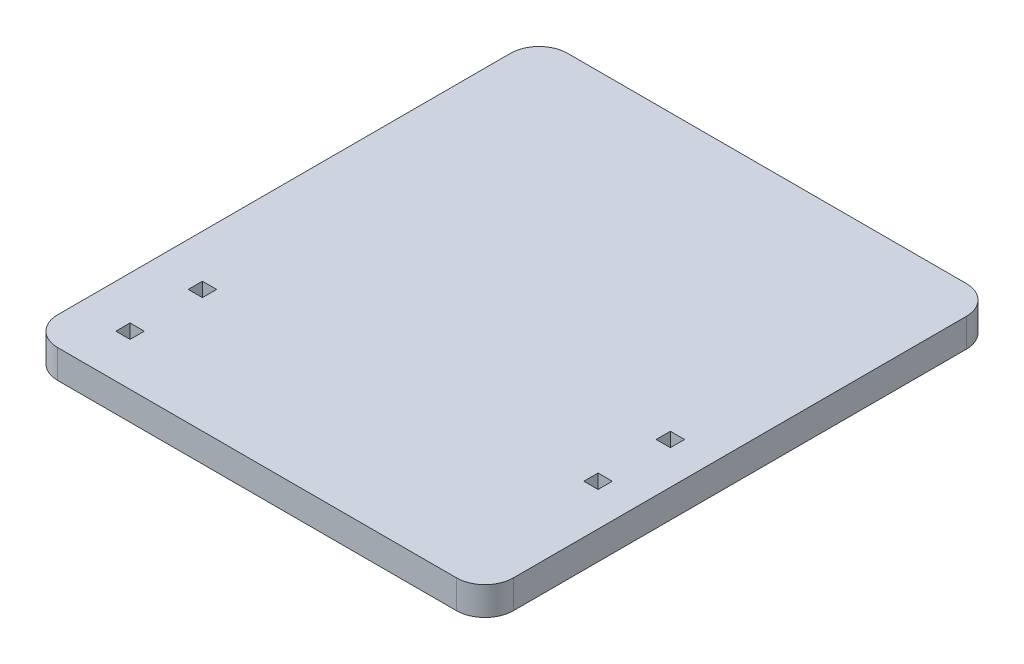
SolidWorks part; units mm, degrees
ref_plane "Front Plane" through (0, 0, 0) normal (0, 0, 1) x (1, 0, 0)
ref_plane "Top Plane" through (0, 0, 0) normal (0, 1, 0) x (1, 0, 0)
ref_plane "Right Plane" through (0, 0, 0) normal (1, 0, 0) x (0, 0, -1)
sketch "Sketch1" plane through (0, 0, 0) normal (0, 1, 0) x (1, 0, 0)
  line L1 (1, 0) -> (15, 0)
  line L2 (0, 1) -> (0, 16.9)
  line L3 (1, 17.9) -> (15, 17.9)
  line L4 (16, 1) -> (16, 16.9)
  line L5 (1.52, 1.52) -> (2.02, 1.52)
  line L6 (1.52, 1.52) -> (1.52, 2.02)
  line L7 (1.52, 2.02) -> (2.02, 2.02)
  line L8 (2.02, 1.52) -> (2.02, 2.02)
  line L9 (1.52, 1.52) -> (2.02, 2.02) construction
  line L10 (1.52, 2.02) -> (2.02, 1.52) construction
  line L11 (1.52, 4.06) -> (2.02, 4.06)
  line L12 (1.52, 4.06) -> (1.52, 4.56)
  line L13 (1.52, 4.56) -> (2.02, 4.56)
  line L14 (2.02, 4.06) -> (2.02, 4.56)
  line L15 (1.52, 4.06) -> (2.02, 4.56) construction
  line L16 (1.52, 4.56) -> (2.02, 4.06) construction
  line L17 (14.298, 7.713) -> (14.798, 7.713)
  line L18 (14.298, 7.713) -> (14.298, 8.213)
  line L19 (14.298, 8.213) -> (14.798, 8.213)
  line L20 (14.798, 7.713) -> (14.798, 8.213)
  line L21 (14.298, 7.713) -> (14.798, 8.213) construction
  line L22 (14.298, 8.213) -> (14.798, 7.713) construction
  line L23 (14.298, 5.173) -> (14.798, 5.173)
  line L24 (14.298, 5.173) -> (14.298, 5.673)
  line L25 (14.298, 5.673) -> (14.798, 5.673)
  line L26 (14.798, 5.173) -> (14.798, 5.673)
  line L27 (14.298, 5.173) -> (14.798, 5.673) construction
  line L28 (14.298, 5.673) -> (14.798, 5.173) construction
  arc A0 (15, 17.9) -> (16, 16.9) centre (15, 16.9) cw
  arc A1 (1, 0) -> (0, 1) centre (1, 1) cw
  arc A2 (15, 0) -> (16, 1) centre (15, 1) ccw
  arc A3 (0, 16.9) -> (1, 17.9) centre (1, 16.9) cw
  point P5 (1.77, 1.77)
  point P10 (1.77, 4.31)
  point P15 (14.548, 7.963)
  point P20 (14.548, 5.423)
  point P25 (13.848, 8.8662)
  point P26 (14.248, 8.2401)
  point P27 (-6.1617, 5.3361)
  point P30 (16, 17.9)
  point P33 (0, 0)
  point P36 (16, 0)
  point P39 (0, 17.9)
  dimension "D12" = 1
  dimension "D1" = 17.9
  dimension "D2" = 16
  dimension "D3" = 1.77
  dimension "D4" = 1.77
  dimension "D5" = 0.5
  dimension "D6" = 0.5
  dimension "D7" = 4.31
  dimension "D8" = 5.423
  dimension "D9" = 7.963
  dimension "D10" = 14.548
  dimension "D11" = 0.5
extrude "Boss-Extrude1" add sketch "Sketch1" along normal blind 1
